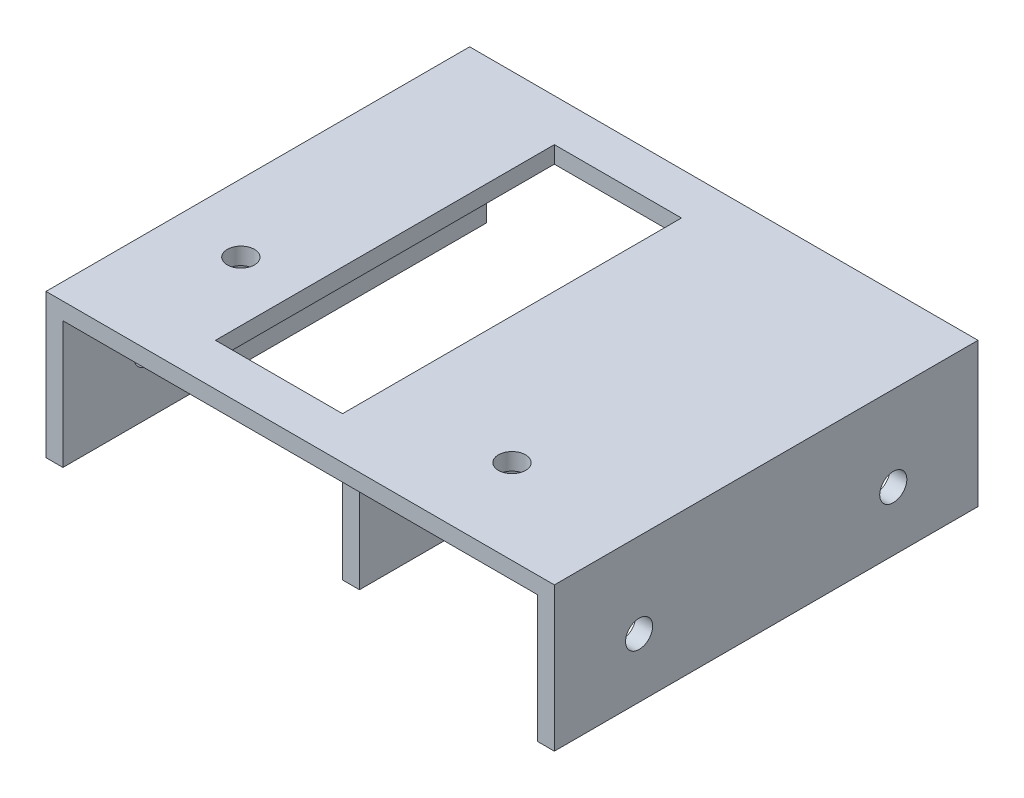
SolidWorks part; units mm, degrees
material "1023 Carbon Steel Sheet (SS)"
ref_plane "Front Plane" through (0, 0, 0) normal (0, 0, 1) x (1, 0, 0)
ref_plane "Top Plane" through (0, 0, 0) normal (0, 1, 0) x (1, 0, 0)
ref_plane "Right Plane" through (0, 0, 0) normal (1, 0, 0) x (0, 0, -1)
sketch "Sketch1" plane through (0, 0, 0) normal (0, 0, 1) x (1, 0, 0)
  line L0 (0, 0) -> (0, 17)
  line L1 (0, 17) -> (60, 17)
  line L2 (60, 17) -> (60, 0)
  line L3 (2, 0) -> (2, 15)
  line L4 (2, 15) -> (58, 15)
  line L5 (58, 15) -> (58, 0)
  line L6 (0, 0) -> (2, 0)
  line L7 (58, 0) -> (60, 0)
  dimension "D1" = 60
  dimension "D2" = 17
  dimension "D3" = 2
extrude "Boss-Extrude1" add sketch "Sketch1" along normal blind 50
sketch "Sketch2" plane through (60, 0, 0) normal (1, 0, 0) x (0, 0, -1)
  line L0 (-50, 0) -> (-50, 17) construction
  line L1 (-50, 17) -> (0, 17) construction
  line L2 (-25, 17) -> (-25, 0) construction
  line L3 (-50, 0) -> (0, 0) construction
  circle A0 centre (-40, 7) radius 1.6
  circle A1 centre (-10, 7) radius 1.6
  dimension "D1" = 3.2
  dimension "D2" = 10
  dimension "D3" = 10
extrude "Cut-Extrude1" cut sketch "Sketch2" against normal through all
sketch "Sketch3" plane through (0, 17, 0) normal (0, 1, 0) x (1, 0, 0)
  line L0 (30, -50) -> (30, 0) construction
  line L1 (60, -50) -> (0, -50) construction
  line L2 (60, 0) -> (0, 0) construction
  line L4 (30, -5) -> (32, -5)
  line L5 (30, -5) -> (30, -45)
  line L6 (30, -45) -> (32, -45)
  line L7 (32, -5) -> (32, -45)
  dimension "D1" = 2
  dimension "D2" = 40
  dimension "D3" = 5
extrude "Boss-Extrude2" add sketch "Sketch3" against normal blind 17
sketch "Sketch5" plane through (32, 0, 0) normal (1, 0, 0) x (0, 0, -1)
  line L1 (-45, 0) -> (-5, 0) construction
  line L2 (-25, 0) -> (-25, 17) construction
  line L3 (-45, 17) -> (-5, 17) construction
  line L4 (-45, 0) -> (-45, 15) construction
  circle A0 centre (-37, 5) radius 1.6
  circle A1 centre (-13, 5) radius 1.6
  dimension "D1" = 3.2
  dimension "D2" = 8
  dimension "D3" = 5
extrude "Cut-Extrude3" cut sketch "Sketch5" against normal blind 2
sketch "Sketch6" plane through (0, 17, 0) normal (0, 1, 0) x (1, 0, 0)
  line L0 (60, -50) -> (0, -50) construction
  line L1 (60, -50) -> (60, 0) construction
  line L2 (0, -50) -> (0, 0) construction
  circle A0 centre (45, -40) radius 1.6
  circle A1 centre (8, -35) radius 1.6
  dimension "D1" = 3.2
  dimension "D2" = 10
  dimension "D4" = 3.2
  dimension "D5" = 8
  dimension "D6" = 15
  dimension "D3" = 15
extrude "Cut-Extrude4" cut sketch "Sketch6" against normal through all
sketch "Sketch7" plane through (0, 15, 0) normal (0, -1, 0) x (1, 0, 0)
  line L1 (30, 5) -> (15, 5)
  line L2 (30, 5) -> (30, 45)
  line L3 (30, 45) -> (15, 45)
  line L4 (15, 5) -> (15, 45)
  dimension "D1" = 40
  dimension "D2" = 15
extrude "Cut-Extrude5" cut sketch "Sketch7" against normal blind 2
